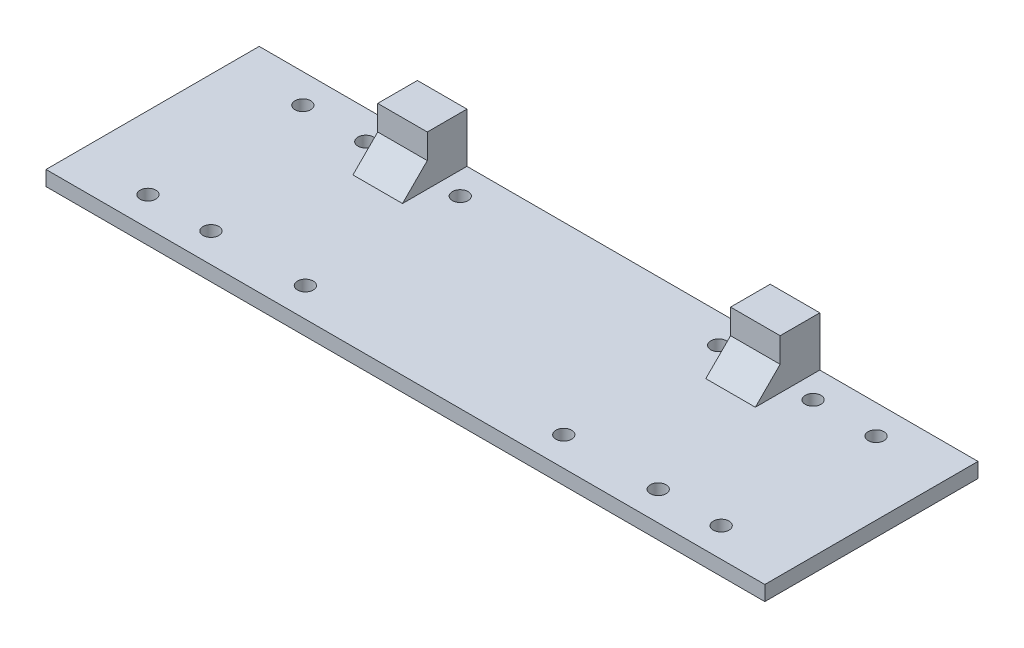
SolidWorks part; units mm, degrees
ref_plane "Front Plane" through (0, 0, 0) normal (0, 0, 1) x (1, 0, 0)
ref_plane "Top Plane" through (0, 0, 0) normal (0, 1, 0) x (1, 0, 0)
ref_plane "Right Plane" through (0, 0, 0) normal (1, 0, 0) x (0, 0, -1)
sketch "Sketch1" plane through (0, 0, 0) normal (0, 1, 0) x (1, 0, 0)
  line L0 (0, 0) -> (-72.5, 0) construction
  line L1 (-72.5, -21.5) -> (72.5, -21.5)
  line L2 (-72.5, -21.5) -> (-72.5, 21.5)
  line L3 (-72.5, 21.5) -> (72.5, 21.5)
  line L4 (72.5, -21.5) -> (72.5, 21.5)
  line L5 (-72.5, -21.5) -> (72.5, 21.5) construction
  line L6 (-72.5, 21.5) -> (72.5, -21.5) construction
  line L8 (0, -21.5) -> (0, 21.5) construction
  circle A0 centre (-57.8125, 15.621) radius 1.5875
  circle A1 centre (-45.1125, 15.621) radius 1.5875
  circle A2 centre (-26.0625, 15.621) radius 1.5875
  circle A3 centre (-26.0625, -15.621) radius 1.5875
  circle A5 centre (-45.1125, -15.621) radius 1.5875
  circle A8 centre (-57.8125, -15.621) radius 1.5875
  circle A9 centre (45.1125, -15.621) radius 1.5875
  circle A10 centre (26.0625, -15.621) radius 1.5875
  circle A11 centre (26.0625, 15.621) radius 1.5875
  circle A12 centre (45.1125, 15.621) radius 1.5875
  circle A13 centre (57.8125, 15.621) radius 1.5875
  circle A14 centre (57.8125, -15.621) radius 1.5875
  point P0 (0, 0)
  dimension "D3" = 145
  dimension "D4" = 43
extrude "Boss-Extrude1" add sketch "Sketch1" along normal blind 3
sketch "Sketch2" plane through (0, 3, 0) normal (0, 1, 0) x (1, 0, 0)
  line L0 (0, -21.5) -> (0, 21.5) construction
  line L1 (-72.5, -21.5) -> (72.5, -21.5) construction
  line L2 (72.5, 21.5) -> (-72.5, 21.5) construction
  line L3 (72.5, 11.5) -> (32.5, 11.5)
  line L4 (-72.5, 21.5) -> (-32.5, 21.5)
  line L5 (-72.5, 21.5) -> (-72.5, 11.5)
  line L6 (-72.5, 11.5) -> (-32.5, 11.5)
  line L7 (-32.5, 21.5) -> (-32.5, 11.5)
  line L8 (32.5, 21.5) -> (32.5, 11.5)
  line L9 (72.5, 21.5) -> (32.5, 21.5)
  line L10 (72.5, 21.5) -> (72.5, 11.5)
  dimension "D1" = 10
  dimension "D2" = 40
extrude "Boss-Extrude2" [suppressed] add sketch "Sketch2" along normal blind 10
chamfer "Chamfer1" [suppressed] distance 20 angle 27
sketch "Sketch3" plane through (0, 0, -21.5) normal (0, 0, -1) x (-1, 0, 0)
  line L0 (0, 0) -> (0, 22.7681) construction
  line L1 (-56.5, 6.5) -> (56.5, 6.5) construction
  line L2 (-72.5, 3) -> (-72.5, 0) construction
  line L3 (-72.5, 0) -> (72.5, 0) construction
  circle A0 centre (-56.5, 6.5) radius 2.2
  circle A1 centre (56.5, 6.5) radius 2.2
  dimension "D1" = 4.4
  dimension "D2" = 16
  dimension "D3" = 6.5
extrude "Cut-Extrude1" [suppressed] cut sketch "Sketch3" against normal blind 5.2
sketch "Sketch4" plane through (0, 3, 0) normal (0, 1, 0) x (1, 0, 0)
  line L0 (-45.1125, 15.621) -> (-26.0625, 15.621) construction
  line L1 (72.5, 21.5) -> (-72.5, 21.5) construction
  line L2 (-30.5875, 13.5) -> (-40.5875, 13.5)
  line L3 (-30.5875, 13.5) -> (-30.5875, 21.5)
  line L4 (-30.5875, 21.5) -> (-40.5875, 21.5)
  line L5 (-40.5875, 13.5) -> (-40.5875, 21.5)
  line L6 (-35.5875, 15.621) -> (-35.5875, 21.5) construction
  line L7 (30.5875, 21.5) -> (40.5875, 21.5)
  line L8 (0, -21.5) -> (0, 21.5) construction
  line L9 (-72.5, -21.5) -> (72.5, -21.5) construction
  line L10 (40.5875, 13.5) -> (40.5875, 21.5)
  line L11 (30.5875, 13.5) -> (40.5875, 13.5)
  line L12 (30.5875, 13.5) -> (30.5875, 21.5)
  point P4 (-35.5875, 15.621)
  dimension "D1" = 10
  dimension "D2" = 8
extrude "Boss-Extrude3" add sketch "Sketch4" along normal blind 10
chamfer "Chamfer2" distance 5 angle 45 2 edges at (35.5875, 3, -13.5) (-35.5875, 3, -13.5)
sketch "Sketch5" plane through (0, 0, -21.5) normal (0, 0, -1) x (-1, 0, 0)
  line L0 (-35.5875, 13) -> (-35.5875, 0) construction
  line L1 (-40.5875, 13) -> (-30.5875, 13) construction
  line L2 (-72.5, 0) -> (72.5, 0) construction
  line L3 (35.5875, 13) -> (35.5875, 0) construction
  line L4 (30.5875, 13) -> (40.5875, 13) construction
  circle A0 centre (-35.5875, 6.5) radius 2.2
  circle A1 centre (35.5875, 6.5) radius 2.2
  dimension "D1" = 4.4
extrude "Cut-Extrude2" cut sketch "Sketch5" against normal blind 5.2
equation "\"width\"=50"
